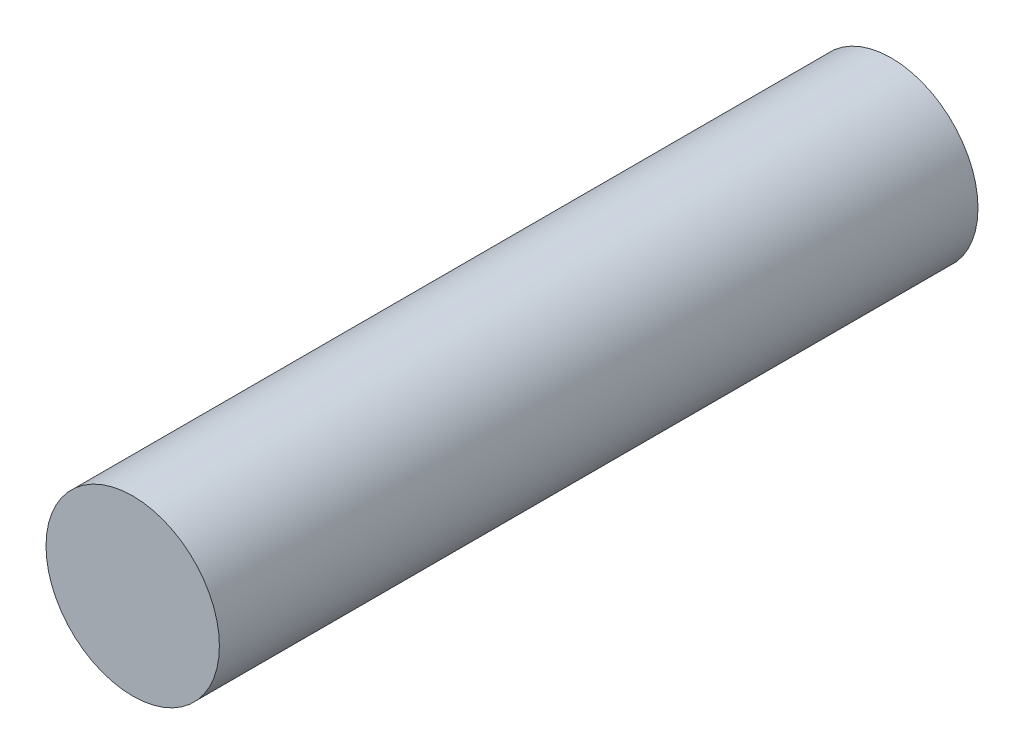
SolidWorks part; units mm, degrees
ref_plane "Front Plane" through (0, 0, 0) normal (0, 0, 1) x (1, 0, 0)
ref_plane "Top Plane" through (0, 0, 0) normal (0, 1, 0) x (1, 0, 0)
ref_plane "Right Plane" through (0, 0, 0) normal (1, 0, 0) x (0, 0, -1)
sketch "Sketch1" plane through (0, 0, 0) normal (0, 0, 1) x (1, 0, 0)
  circle A0 centre (0, 0) radius 4
  dimension "D1" = 8
extrude "Boss-Extrude1" add sketch "Sketch1" along normal blind 35
